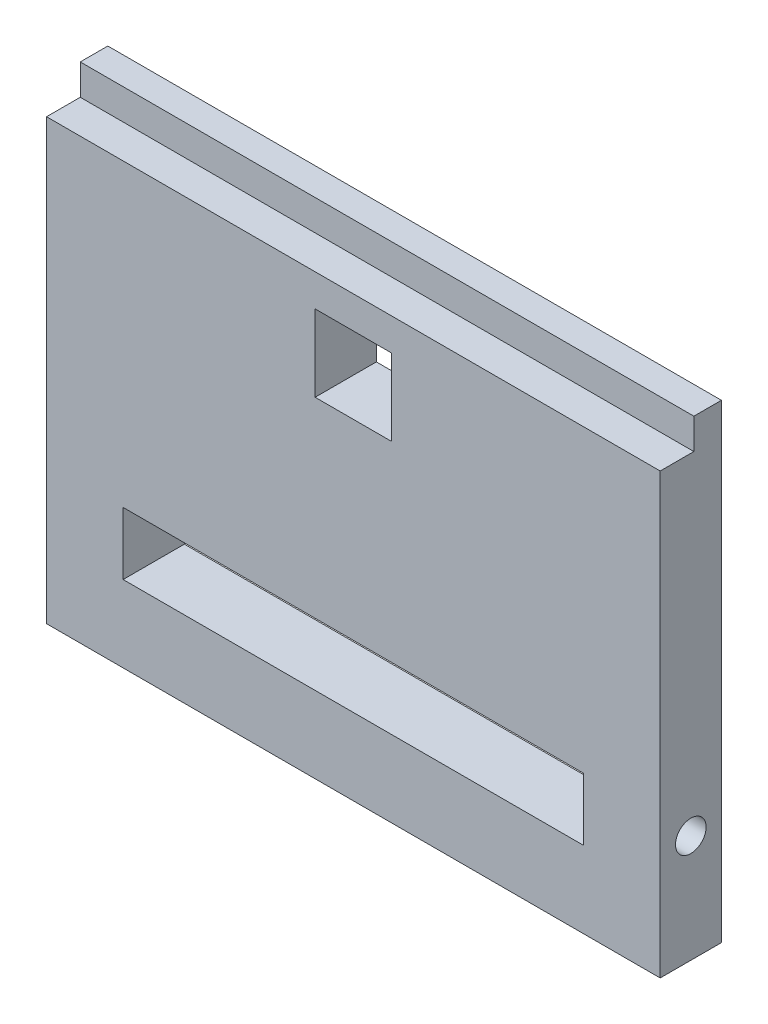
SolidWorks part; units mm, degrees
ref_plane "Front Plane" through (0, 0, 0) normal (0, 0, 1) x (1, 0, 0)
ref_plane "Top Plane" through (0, 0, 0) normal (0, 1, 0) x (1, 0, 0)
ref_plane "Right Plane" through (0, 0, 0) normal (1, 0, 0) x (0, 0, -1)
sketch "Sketch1" plane through (0, 0, 0) normal (0, 0, 1) x (1, 0, 0)
  line L0 (-75.2, 10.2) -> (75.2, 10.2)
  line L1 (-75, -10) -> (75, -10) construction
  line L2 (-75, -10) -> (-75, 10) construction
  line L3 (-75, 10) -> (75, 10) construction
  line L4 (75, -10) -> (75, 10) construction
  line L5 (-75, -10) -> (75, 10) construction
  line L6 (-75, 10) -> (75, -10) construction
  line L7 (75.2, -10.2) -> (75.2, 10.2)
  line L8 (-75.2, -10.2) -> (75.2, -10.2)
  line L9 (-75.2, -10.2) -> (-75.2, 10.2)
  line L10 (-100.2, 35.2) -> (100.2, 35.2)
  line L11 (100.2, -35.2) -> (100.2, 35.2)
  line L12 (-100.2, -35.2) -> (100.2, -35.2)
  line L13 (-100.2, -35.2) -> (-100.2, 35.2)
  point P0 (0, 0)
  point P14 (0, 10.2)
  dimension "D1" = 150
  dimension "D2" = 20
  dimension "D3" = 0.2
  dimension "D4" = 25
sketch "Sketch2" plane through (0, 0, 0) normal (0, 0, 1) x (1, 0, 0)
  line L1 (100.2, -35.2) -> (100.2, 35.2) construction
  line L2 (-100.2, -35.2) -> (100.2, -35.2) construction
  line L3 (-100.2, -35.2) -> (-100.2, 35.2) construction
  line L4 (-75.2, 10.2) -> (75.2, 10.2) construction
  line L5 (75.2, -10.2) -> (75.2, 10.2) construction
  line L6 (-75.2, -10.2) -> (75.2, -10.2) construction
  line L7 (-75.2, -10.2) -> (-75.2, 10.2) construction
  line L9 (100.2, -35.2) -> (100.2, 118.2)
  line L10 (-100.2, -35.2) -> (100.2, -35.2)
  line L11 (-100.2, -35.2) -> (-100.2, 118.2)
  line L12 (-75.2, 10.2) -> (75.2, 10.2)
  line L13 (75.2, -10.2) -> (75.2, 10.2)
  line L14 (-75.2, -10.2) -> (75.2, -10.2)
  line L15 (-75.2, -10.2) -> (-75.2, 10.2)
  line L16 (-100.2, 118.2) -> (100.2, 118.2)
  dimension "D1" = 108
extrude "Boss-Extrude1" add sketch "Sketch2" along normal mid plane 20
sketch "Sketch3" plane through (100.2, 0, 0) normal (1, 0, 0) x (0, 0, -1)
  line L0 (0, -20.2) -> (0, 20.2) construction
  line L4 (10, -10.2) -> (10, 10.2)
  line L5 (10, 10.2) -> (-10, 10.2)
  line L6 (-10, 10.2) -> (-10, -10.2)
  line L7 (-10, -10.2) -> (10, -10.2)
  line L8 (10, -10.2) -> (10, 10.2)
  line L10 (-10, 10.2) -> (-10, -10.2)
  line L13 (10, -35.2) -> (10, 118.2)
  line L14 (10, 118.2) -> (-10, 118.2)
  line L15 (-10, 118.2) -> (-10, -35.2)
  line L16 (-10, -35.2) -> (10, -35.2)
  line L17 (10, -20.2) -> (10, 20.2)
  line L19 (-10, 20.2) -> (-10, -20.2)
  circle A0 centre (0, 0) radius 5
  circle A1 centre (0, 20.2) radius 1
  circle A2 centre (0, -20.2) radius 1
  arc A3 (10, 20.2) -> (-10, 20.2) centre (0, 20.2) ccw
  arc A4 (-10, -20.2) -> (10, -20.2) centre (0, -20.2) ccw
  point P11 (0, 0)
  dimension "D2" = 10
  dimension "D3" = 2
  dimension "D4" = 0
  dimension "D5" = 40.4
  dimension "D1" = 0
sketch "Sketch4" plane through (100.2, 0, 0) normal (1, 0, 0) x (0, 0, -1)
  circle A0 centre (0, 0) radius 5 construction
  circle A1 centre (0, 0) radius 5
extrude "Cut-Extrude1" cut sketch "Sketch4" against normal up to next
sketch "Sketch6" plane through (0, 0, 10) normal (0, 0, 1) x (1, 0, 0)
  line L0 (12.5, 72.7) -> (12.5, 97.7) construction
  line L1 (12.5, 97.7) -> (-12.5, 97.7) construction
  line L2 (-75, 119.2) -> (-75, 10.2) construction
  line L3 (75, 119.2) -> (-75, 119.2) construction
  line L4 (75, 10.2) -> (75, 119.2) construction
  line L5 (-75, 10.2) -> (75, 10.2) construction
  line L6 (-12.5, 97.7) -> (-12.5, 72.7) construction
  line L7 (-12.5, 72.7) -> (12.5, 72.7) construction
sketch "Sketch7" plane through (0, 0, 10) normal (0, 0, 1) x (1, 0, 0)
  line L0 (12.5, 97.7) -> (-12.5, 97.7) construction
  line L1 (-12.5, 97.7) -> (-12.5, 72.7) construction
  line L2 (-12.5, 72.7) -> (12.5, 72.7) construction
  line L3 (12.5, 72.7) -> (12.5, 97.7) construction
  line L4 (12.5, 97.7) -> (-12.5, 97.7)
  line L5 (-12.5, 97.7) -> (-12.5, 72.7)
  line L6 (-12.5, 72.7) -> (12.5, 72.7)
  line L7 (12.5, 72.7) -> (12.5, 97.7)
extrude "Cut-Extrude2" cut sketch "Sketch7" against normal through all both and the other way through all
sketch "Sketch8" plane through (0, 118.2, 0) normal (0, 1, 0) x (1, 0, 0)
  line L1 (-100.2, -10) -> (100.2, -10)
  line L2 (-100.2, -10) -> (-100.2, 1)
  line L3 (-100.2, 1) -> (100.2, 1)
  line L4 (100.2, 10) -> (-100.2, 10)
  line L5 (-100.2, 10) -> (-100.2, -10)
  line L6 (-100.2, -10) -> (100.2, -10)
  line L7 (100.2, -10) -> (100.2, 10)
  line L8 (100.2, 10) -> (-100.2, 10) construction
  line L9 (-100.2, 10) -> (-100.2, -10) construction
  line L10 (-100.2, -10) -> (100.2, -10) construction
  line L11 (100.2, -10) -> (100.2, 10) construction
  line L12 (100.2, -10) -> (100.2, 1)
  dimension "D2" = 9
  dimension "D1" = 0
extrude "Cut-Extrude3" cut sketch "Sketch8" against normal blind 10
